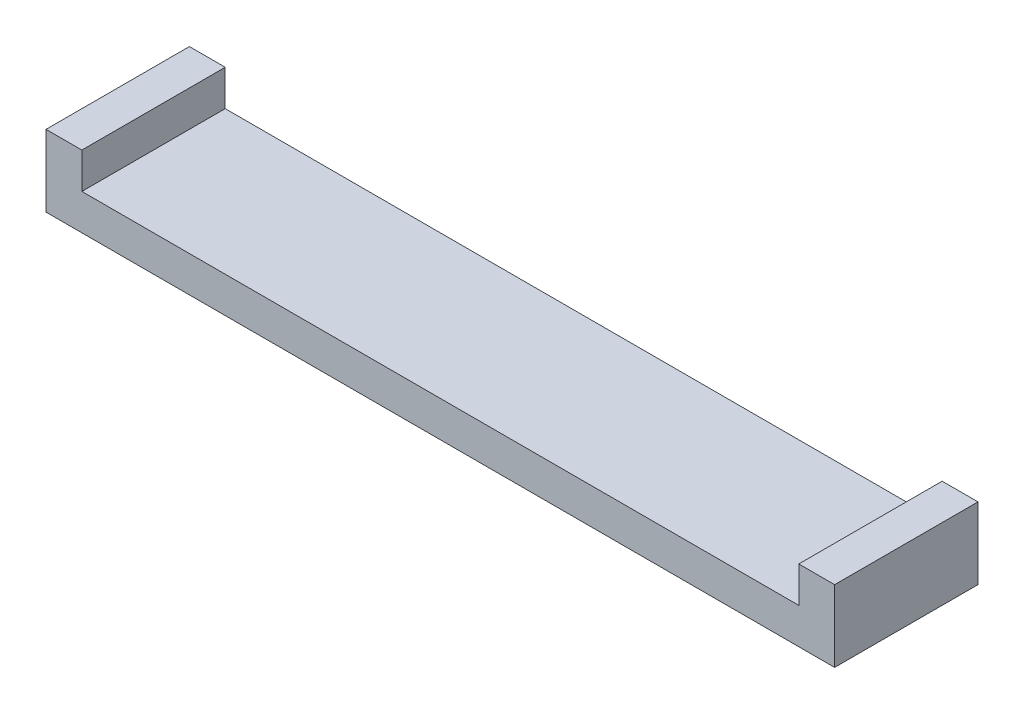
SolidWorks part; units mm, degrees
ref_plane "Front Plane" through (0, 0, 0) normal (0, 0, 1) x (1, 0, 0)
ref_plane "Top Plane" through (0, 0, 0) normal (0, 1, 0) x (1, 0, 0)
ref_plane "Right Plane" through (0, 0, 0) normal (1, 0, 0) x (0, 0, -1)
sketch "Sketch1" plane through (0, 0, 0) normal (0, 0, 1) x (1, 0, 0)
  line L0 (-5, -5) -> (105, -5)
  line L1 (105, -5) -> (105, 5)
  line L2 (105, 5) -> (100, 5)
  line L3 (100, 5) -> (100, 0)
  line L4 (100, 0) -> (0, 0)
  line L5 (0, 0) -> (0, 5)
  line L6 (0, 5) -> (-5, 5)
  line L7 (-5, 5) -> (-5, -5)
extrude "Boss-Extrude1" add sketch "Sketch1" along normal blind 20
